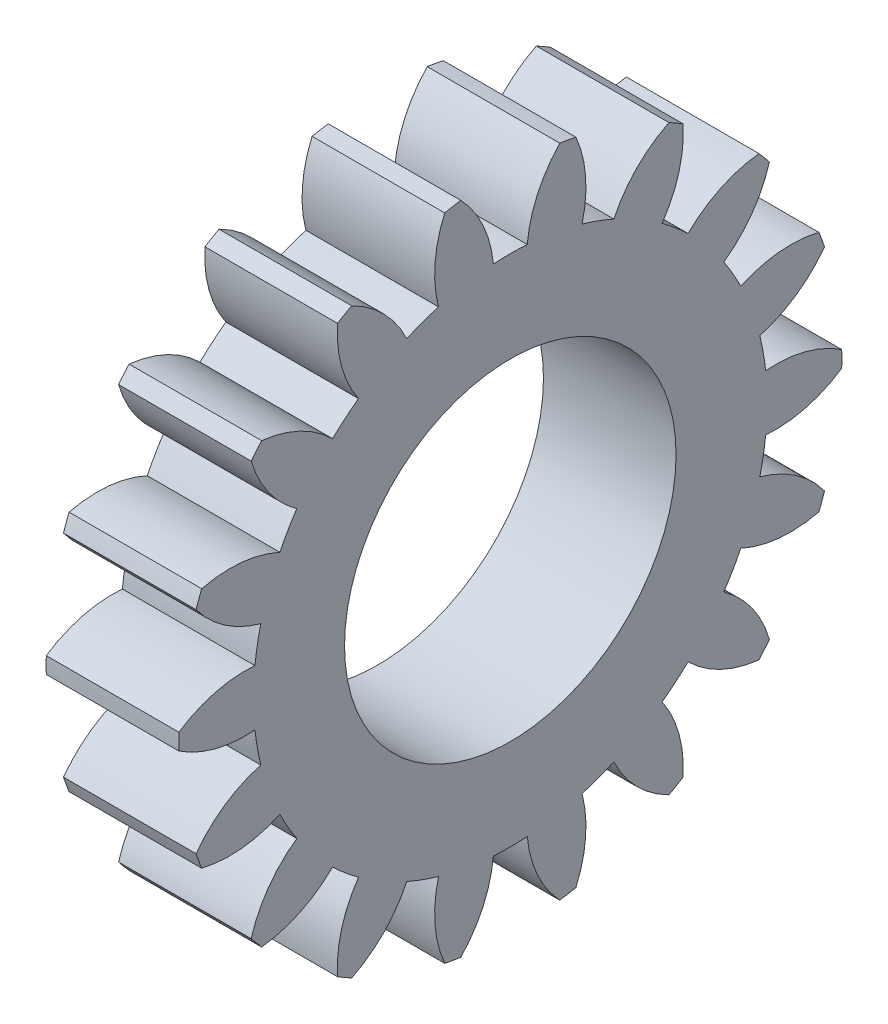
SolidWorks part; units mm, degrees
ref_plane "Plane1" through (0, 0, 0) normal (0, 0, 1) x (1, 0, 0)
ref_plane "Plane2" through (0, 0, 0) normal (0, 1, 0) x (1, 0, 0)
ref_plane "Plane3" through (0, 0, 0) normal (1, 0, 0) x (0, 0, -1)
sketch "HoldingSke" plane through (0, 0, 0) normal (0, 1, 0) x (1, 0, 0)
  line L0 (0, 0) -> (0.9511, -0.309)
  line L1 (-15, 0) -> (100, 0) construction
  line L2 (0, 0) -> (-2.1039, 2.3779)
  line L3 (0, 0) -> (-11.863, 4.5341)
  line L4 (0, 0) -> (8.2133, 2.6687)
  line L5 (0, 0) -> (-46.8476, -17.4728)
  line L6 (0, 0) -> (-3.3159, -2.2372)
  line L7 (-2.1039, 2.3779) -> (8.6586, 51.2059)
  line L8 (-76.2, 54.61) -> (-74.4, 54.61)
  line L9 (-71.009, 38.7566) -> (-53.1078, 45.2721)
  line L10 (-76.2, 71.12) -> (104.1128, 71.12)
  line L11 (0, 0) -> (-4, 0)
  line L12 (-76.2, 101.6) -> (-76.162, 101.6)
  line L13 (24.9733, 27.94) -> (52.9518, 28.4284)
  line L14 (24.9733, 27.94) -> (24.9743, 27.94)
  line L15 (24.9733, 27.94) -> (100.4006, 29.5858)
  line L16 (-63.627, -1) -> (-12.827, -1)
  circle A0 centre (0, 0) radius 5
  circle A1 centre (0, 0) radius 7.749
  circle A2 centre (0, 0) radius 37.5
  circle A3 centre (0, 0) radius 5
  dimension "MHD" = 15.498
  dimension "Hub_dia" = 75
  dimension "Bore" = 10
  dimension "MBD" = 10
  dimension "Num_teeth" = 18
  dimension "Pitch" = 1
  dimension "Overall_len" = 50
  dimension "Show_teeth" = 18
  dimension "Thickness" = 4
  dimension "OAL" = 50.0001
  dimension "T_dim" = 1.8
  dimension "Ap" = 20
  dimension "H" = 19.05
  dimension "Pitch_radius" = 180.3128
  dimension "Width" = 4
  dimension "Backlash" = 0.038
  dimension "Addendum_fac" = 1
  dimension "Dedendum_fac" = 1.25
  dimension "Clearance_fac" = 0.25
  dimension "Dedendum_add" = 0.001
  dimension "Module" = 1
sketch "BasProSke" plane through (0, 0, 0) normal (0, 1, 0) x (1, 0, 0)
  line L0 (-10, 0) -> (60, 0) construction
  line L1 (0, 0) -> (0, 10)
  line L2 (0, 0) -> (4, 0)
  line L3 (4, 0) -> (4, 10)
  line L4 (4, 10) -> (0, 10)
  dimension "Thickness" = 4
  dimension "Diameter" = 20
revolve "Base-Revolve" add sketch "BasProSke" angle 360 about L0
sketch "TooCutSke" plane through (0, 0, 0) normal (1, 0, 0) x (0, 0, -1)
  line L1 (0, 0) -> (0, 107) construction
  line L2 (0, 0) -> (-0.8509, 8.9597) construction
  line L3 (0, 0) -> (-3.1157, 17.6701) construction
  line L4 (-0.8509, 8.9597) -> (-1.5579, 8.835) construction
  arc A0 (0.5106, 7.7322) -> (-0.5106, 7.7322) centre (0, 0) ccw
  arc A1 (1.5152, 9.9102) -> (-1.5152, 9.9102) centre (0, 0) ccw
  circle A2 centre (0, 0) radius 9 construction
  circle A3 centre (0, 0) radius 8.4572 construction
  arc A4 (-0.5106, 7.7322) -> (-1.5152, 9.9102) centre (-4.0952, 7.3996) ccw
  arc A5 (1.5152, 9.9102) -> (0.5106, 7.7322) centre (4.0952, 7.3996) ccw
  dimension "Root_dia" = 15.498
  dimension "Overcut_dia" = 20.0508
  dimension "Pitch_dia" = 18
  dimension "Base_dia" = 16.9145
  dimension "Flank_rad" = 3.6
  dimension "Half_ang" = 10
  dimension "Half_CT" = 0.7179
extrude "ToothCut" cut sketch "TooCutSke" along normal through all
fillet "Breaks" [suppressed] radius 0.02
fillet "RootFillets" [suppressed] radius 0.251
pattern_circular "TeethCuts" count 18 every 20 about axis through (-10, 0, 0) along (1, 0, 0) of "ToothCut", "RootFillets", "Breaks"
sketch "HubNeaOneSke" plane through (0, 0, 0) normal (-1, 0, 0) x (0, 0, 1)
  circle A0 centre (0, 0) radius 7.749
  dimension "Diameter" = 15.498
extrude "HubNearOne" [suppressed] add sketch "HubNeaOneSke" along normal blind 46.0001
sketch "HubNeaBotSke" plane through (0, 0, 0) normal (-1, 0, 0) x (0, 0, 1)
  circle A0 centre (0, 0) radius 7.749
  dimension "Diameter" = 15.498
extrude "HubNearBoth" [suppressed] add sketch "HubNeaBotSke" along normal blind 23
ref_plane "FarPln" through (4, 0, 0) normal (1, 0, 0) x (0, 0, -1)
sketch "HubFarSke" plane through (4, 0, 0) normal (1, 0, 0) x (0, 0, -1)
  circle A0 centre (0, 0) radius 7.749
  dimension "Diameter" = 15.498
extrude "HubFar" [suppressed] add sketch "HubFarSke" along normal blind 23
sketch "BorSke" plane through (0, 0, 0) normal (1, 0, 0) x (0, 0, -1)
  circle A0 centre (0, 0) radius 5
  dimension "Diameter" = 10
extrude "Bore" cut sketch "BorSke" along normal mid plane 100.0001
sketch "KeySke" plane through (0, 0, 0) normal (1, 0, 0) x (0, 0, -1)
  line L0 (-2, 0) -> (-2, 6.8)
  line L1 (-2, 6.8) -> (2, 6.8)
  line L2 (2, 6.8) -> (2, 0)
  line L3 (0, 0) -> (0, 34) construction
  line L4 (-2, 0) -> (2, 0)
  dimension "Width" = 4
  dimension "Offset" = 6.8
extrude "Keyway" [suppressed] cut sketch "KeySke" along normal mid plane 100.0001
pattern_circular "Keyway2" [suppressed] count 2 every 90 about axis through (-10, 0, 0) along (1, 0, 0)
sketch "Sketch1" plane through (4, 0, 0) normal (1, 0, 0) x (0, 0, -1)
  circle A0 centre (0, 0) radius 10
equation "' \"Module@HoldingSke\" = 6.35"
equation "' \"Num_teeth@HoldingSke\" = 12"
equation "' \"Ap@HoldingSke\" =  20"
equation "' \"Ap@HoldingSke\" = 20"
equation "' \"Width@HoldingSke\" = 0.5 * 25.4"
equation "' \"Hub_dia@HoldingSke\"= 1 * 25.4"
equation "' \"Hub_dia@HoldingSke\" = 1 * 25.4"
equation "' \"Overall_len@HoldingSke\" = 1.0 * 25.4"
equation "' \"Bore@HoldingSke\" = 0.75 * 25.4"
equation "' \"T_dim@HoldingSke\" = 0.1 * 25.4"
equation "' \"Width@KeySke\" = 0.25 * 25.4"
equation "' \"Show_teeth@HoldingSke\" = 13"
equation "' \"Backlash@HoldingSke\" = 0.009 * 25.4"
equation "' \"Addendum_fac@HoldingSke\" = 1.0"
equation "' \"Dedendum_fac@HoldingSke\" = 1.25"
equation "' \"Dedendum_add@HoldingSke\" = 0.00005 * 25.4"
equation "' \"Clearance_fac@HoldingSke\" = 0.25"
equation "\"Pitch@HoldingSke\" = 1 / \"Module@HoldingSke\""
equation "\"Overcut_dia@TooCutSke\" = (\"Num_teeth@HoldingSke\" + 2 * \"Addendum_fac@HoldingSke\") / \"Pitch@HoldingSke\" + 0.002 * 25.4"
equation "\"Pitch_dia@TooCutSke\" = \"Num_teeth@HoldingSke\" / \"Pitch@HoldingSke\""
equation "\"Base_dia@TooCutSke\" = \"Num_teeth@HoldingSke\" / \"Pitch@HoldingSke\" * cos((\"Ap@HoldingSke\"  * 3.14159265 / 180))"
equation "\"Root_dia@TooCutSke\" = (\"Num_teeth@HoldingSke\" + 2) / \"Pitch@HoldingSke\" - 2 * (\"Addendum_fac@HoldingSke\" + \"Dedendum_fac@HoldingSke\") / \"Pitch@HoldingSke\" - \"Dedendum_add@HoldingSke\" * 2"
equation "\"Half_ang@TooCutSke\" = 180 / \"Num_teeth@HoldingSke\""
equation "\"Half_CT@TooCutSke\" = \"Num_teeth@HoldingSke\" / \"Pitch@HoldingSke\" * sin((3.14159265 / 2 / \"Num_teeth@HoldingSke\")) / 2 - 7 * \"Backlash@HoldingSke\" / 4"
equation "\"Flank_rad@TooCutSke\" = \"Num_teeth@HoldingSke\" / \"Pitch@HoldingSke\" / 5"
equation "\"Radius@RootFillets\" = \"Clearance_fac@HoldingSke\" / \"Pitch@HoldingSke\" + \"Dedendum_add@HoldingSke\""
equation "\"Break_rad@Breaks\" = 0.02 / \"Pitch@HoldingSke\""
equation "\"Thickness@HoldingSke\" = \"Width@HoldingSke\""
equation "\"OAL@HoldingSke\" = \"Thickness@HoldingSke\""
equation "\"MHD@HoldingSke\" = (\"Num_teeth@HoldingSke\" + 2) / \"Pitch@HoldingSke\" - 2 * (\"Addendum_fac@HoldingSke\" + \"Dedendum_fac@HoldingSke\")  / \"Pitch@HoldingSke\" - \"Dedendum_add@HoldingSke\" * 2"
equation "\"MBD@HoldingSke\" = (\"Num_teeth@HoldingSke\" + 2) / \"Pitch@HoldingSke\" - 2 * (\"Addendum_fac@HoldingSke\" + \"Dedendum_fac@HoldingSke\")  / \"Pitch@HoldingSke\" - \"Dedendum_add@HoldingSke\" * 2 - 0.002 * 25.4"
equation "\"MHD@HoldingSke\" = ((sgn( \"MHD@HoldingSke\" - \"Hub_dia@HoldingSke\" )-1)*( \"MHD@HoldingSke\" - \"Hub_dia@HoldingSke\" ))/-2+ \"Hub_dia@HoldingSke\""
equation "\"MBD@HoldingSke\" = ((sgn( \"MBD@HoldingSke\" - \"Bore@HoldingSke\" )-1)*( \"MBD@HoldingSke\" - \"Bore@HoldingSke\" ))/-2+ \"Bore@HoldingSke\""
equation "\"OAL@HoldingSke\" = ((sgn( \"OAL@HoldingSke\" - \"Overall_len@HoldingSke\" )+1)*( \"OAL@HoldingSke\" - \"Overall_len@HoldingSke\" ))/2 + \"Overall_len@HoldingSke\" + 0.000002 * 25.4"
equation "\"Num_teeth@TeethCuts\" = int( \"Show_teeth@HoldingSke\" ) + 1"
equation "\"Num_teeth@TeethCuts\" = ((sgn( \"Num_teeth@TeethCuts\" - \"Num_teeth@HoldingSke\" )-1)*( \"Num_teeth@TeethCuts\" - \"Num_teeth@HoldingSke\" ))/-2+ \"Num_teeth@HoldingSke\""
equation "\"Num_teeth@TeethCuts\" = ((sgn( \"Num_teeth@TeethCuts\" - 2.0)+1)*( \"Num_teeth@TeethCuts\" - 2.0))/2 +2.0"
equation "\"Angle@TeethCuts\" = 360.0 / \"Num_teeth@HoldingSke\""
equation "\"Diameter@BasProSke\" = (\"Num_teeth@HoldingSke\" + 2 * \"Addendum_fac@HoldingSke\") / \"Pitch@HoldingSke\""
equation "\"Thickness@BasProSke\"  = \"Thickness@HoldingSke\""
equation "' \"Fillet_rad@BasProSke\" =  \"Thickness@HoldingSke\" * 0.05"
equation "' \"Fillet_rad@BasProSke\" = \"Thickness@HoldingSke\" * 0.05"
equation "\"MHD@HoldingSke\" = ((sgn( \"MHD@HoldingSke\" - \"Root_dia@TooCutSke\" )-1)*( \"MHD@HoldingSke\" - \"Root_dia@TooCutSke\" ))/-2+ \"Root_dia@TooCutSke\""
equation "\"Diameter@HubNeaOneSke\" = \"MHD@HoldingSke\""
equation "\"Length@HubNearOne\" = \"OAL@HoldingSke\" - \"Thickness@BasProSke\""
equation "\"Diameter@HubNeaBotSke\" = \"MHD@HoldingSke\""
equation "\"Length@HubNearBoth\" = ( \"OAL@HoldingSke\" - \"Thickness@BasProSke\" ) / 2.0"
equation "\"Thickness@FarPln\" = \"Thickness@BasProSke\""
equation "\"Diameter@HubFarSke\" = \"MHD@HoldingSke\""
equation "\"Length@HubFar\" = ( \"OAL@HoldingSke\" - \"Thickness@BasProSke\" ) / 2.0"
equation "\"Diameter@BorSke\" = \"MBD@HoldingSke\""
equation "\"D1@Bore\" = \"OAL@HoldingSke\" * 2.0"
equation "\"D1@Keyway\" = \"OAL@HoldingSke\" * 2.0"
equation "\"Offset@KeySke\" = \"T_dim@HoldingSke\" + \"MBD@HoldingSke\" / 2.0"
